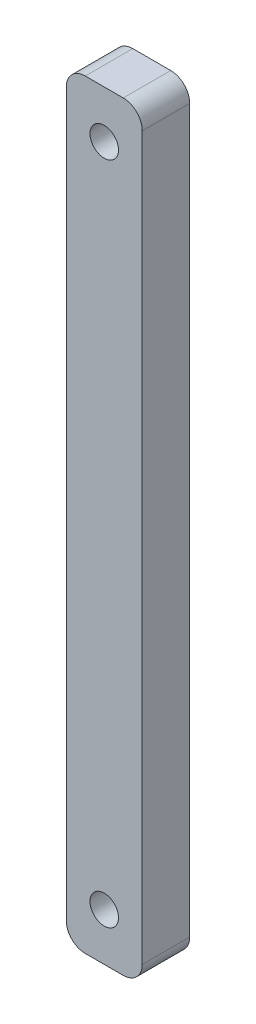
SolidWorks part; units mm, degrees
ref_plane "前视基准面" through (0, 0, 0) normal (0, 0, 1) x (1, 0, 0)
ref_plane "上视基准面" through (0, 0, 0) normal (0, 1, 0) x (1, 0, 0)
ref_plane "右视基准面" through (0, 0, 0) normal (1, 0, 0) x (0, 0, -1)
sketch "草图1" plane through (0, 0, 0) normal (0, 0, 1) x (1, 0, 0)
  line L1 (4, -40) -> (-4, -40)
  line L2 (4, -40) -> (4, 40)
  line L3 (4, 40) -> (-4, 40)
  line L4 (-4, -40) -> (-4, 40)
  line L5 (4, -40) -> (-4, 40) construction
  line L6 (4, 40) -> (-4, -40) construction
  point P0 (0, 0)
  dimension "D1" = 8
  dimension "D2" = 80
extrude "凸台-拉伸1" add sketch "草图1" along normal blind 5
sketch "草图2" plane through (0, 0, 5) normal (0, 0, 1) x (1, 0, 0)
  line L0 (0, -40) -> (0, -35) construction
  line L1 (-4, -40) -> (4, -40) construction
  line L2 (0, 40) -> (0, 35) construction
  line L3 (4, 40) -> (-4, 40) construction
  circle A0 centre (0, 35) radius 1.5
  circle A1 centre (0, -35) radius 1.5
  dimension "D3" = 3
  dimension "D4" = 3
  dimension "D1" = 5
  dimension "D2" = 5
extrude "切除-拉伸1" cut sketch "草图2" against normal through all
fillet "圆角1" radius 2 4 edges at (-4, -40, 2.5) (4, -40, 2.5) (4, 40, 2.5) (-4, 40, 2.5)
